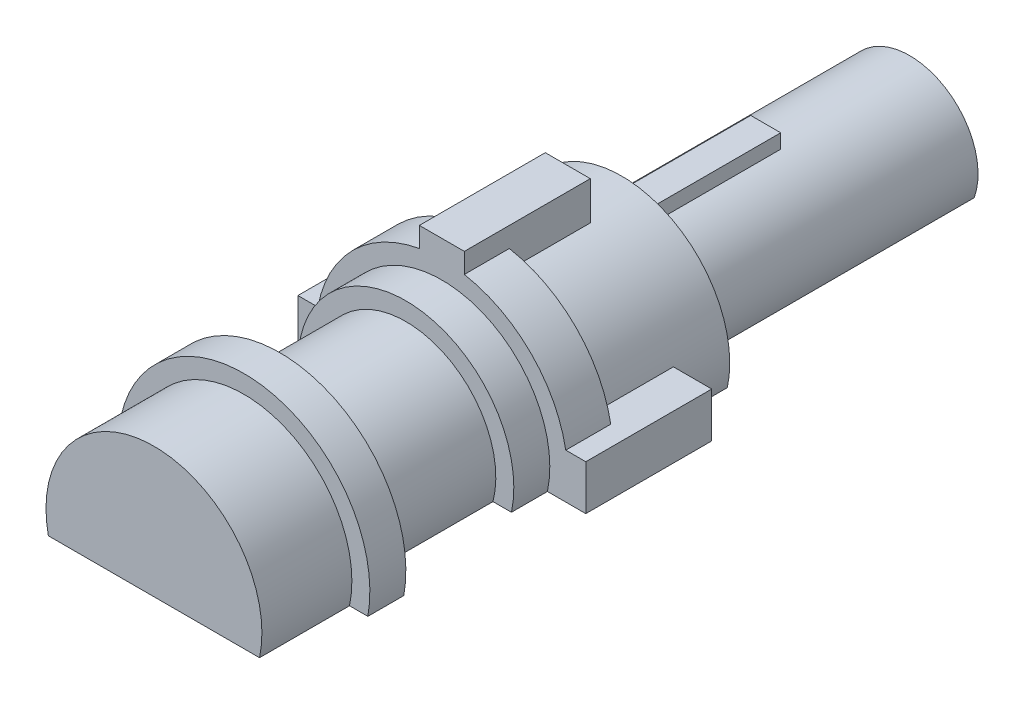
SolidWorks part; units mm, degrees
ref_plane "Front Plane" through (0, 0, 0) normal (0, 0, 1) x (1, 0, 0)
ref_plane "Top Plane" through (0, 0, 0) normal (0, 1, 0) x (1, 0, 0)
ref_plane "Right Plane" through (0, 0, 0) normal (1, 0, 0) x (0, 0, -1)
sketch "Sketch1" plane through (0, 0, 0) normal (0, 0, 1) x (1, 0, 0)
  line L0 (-11.1312, -1.25) -> (14.2968, -1.25) construction
  line L1 (-11.6369, 1.25) -> (-5.8683, 1.25) construction
  line L3 (8, 1.25) -> (5.8683, 1.25)
  line L4 (8, 1.25) -> (8, -1.25)
  line L5 (8, -1.25) -> (-8, -1.25)
  line L6 (-8, 1.25) -> (-8, -1.25)
  line L9 (-1.25, 8) -> (1.25, 8)
  line L10 (-1.25, 8) -> (-1.25, 5.8683)
  line L12 (1.25, 8) -> (1.25, 5.8683)
  line L18 (-5.8683, 1.25) -> (-8, 1.25)
  line L24 (5.8683, 1.25) -> (15.6333, 1.25) construction
  arc A2 (5.8683, 1.25) -> (1.25, 5.8683) centre (0, 0) ccw
  arc A3 (-1.25, 5.8683) -> (-5.8683, 1.25) centre (0, 0) ccw
  dimension "D2" = 1.25
  dimension "D3" = 2.5
  dimension "D4" = 16
  dimension "D6" = 2.5
extrude "Boss-Extrude1" add sketch "Sketch1" along normal blind 7
sketch "Sketch3" plane through (0, 0, 7) normal (0, 0, 1) x (1, 0, 0)
  line L0 (-5.8683, -1.25) -> (5.8683, -1.25)
  arc A0 (5.8683, -1.25) -> (-5.8683, -1.25) centre (0, 0) ccw
extrude "Boss-Extrude2" add sketch "Sketch3" along normal blind 16
sketch "Sketch5" plane through (0, 0, 23) normal (0, 0, 1) x (1, 0, 0)
  line L0 (-6.8875, -1.25) -> (6.8875, -1.25)
  arc A0 (6.8875, -1.25) -> (-6.8875, -1.25) centre (0, 0) ccw
extrude "Boss-Extrude3" add sketch "Sketch5" against normal blind 2.5 from offset 16 offset against normal yes
sketch "Sketch6" plane through (0, 0, 23) normal (0, 0, 1) x (1, 0, 0)
  line L0 (-6.8875, -1.25) -> (6.8875, -1.25)
  arc A0 (6.8875, -1.25) -> (-6.8875, -1.25) centre (0, 0) ccw
extrude "Boss-Extrude4" add sketch "Sketch6" against normal blind 2.5 from offset 5 offset against normal yes
sketch "Sketch7" plane through (0, 0, 23) normal (0, 0, 1) x (1, 0, 0)
  line L0 (-4.8412, -1.25) -> (4.8412, -1.25)
  arc A0 (4.8412, -1.25) -> (-4.8412, -1.25) centre (0, 0) ccw
  circle A1 centre (0, 0) radius 7.5818
  dimension "D1" = 10
extrude "Cut-Extrude1" cut sketch "Sketch7" against normal blind 7 from offset 7 offset against normal yes
sketch "Sketch8" plane through (0, 0, 0) normal (0, 0, -1) x (-1, 0, 0)
  line L0 (-5.8683, -1.25) -> (5.8683, -1.25)
  arc A0 (5.8683, -1.25) -> (-5.8683, -1.25) centre (0, 0) ccw
extrude "Boss-Extrude5" add sketch "Sketch8" along normal blind 3
sketch "Sketch9" plane through (0, 0, -3) normal (0, 0, -1) x (-1, 0, 0)
  line L0 (-3.5885, -1.25) -> (3.5885, -1.25)
  line L3 (0.8333, 4.5) -> (-0.8333, 4.5)
  line L7 (-0.8333, 3.7075) -> (-0.8333, 4.5)
  line L10 (0.8333, 3.7075) -> (0.8333, 4.5)
  arc A3 (-0.8333, 3.7075) -> (-3.5885, -1.25) centre (0, 0) ccw
  arc A4 (3.5885, -1.25) -> (0.8333, 3.7075) centre (0, 0) ccw
  dimension "D1" = 5.75
  dimension "D2" = 1.6667
  dimension "D3" = 3.8
extrude "Boss-Extrude6" add sketch "Sketch9" along normal blind 8
sketch "Sketch10" plane through (0, 0, -11) normal (0, 0, -1) x (-1, 0, 0)
  line L0 (-3.5885, -1.25) -> (3.5885, -1.25)
  arc A0 (3.5885, -1.25) -> (-3.5885, -1.25) centre (0, 0) ccw
extrude "Boss-Extrude7" add sketch "Sketch10" along normal blind 8
